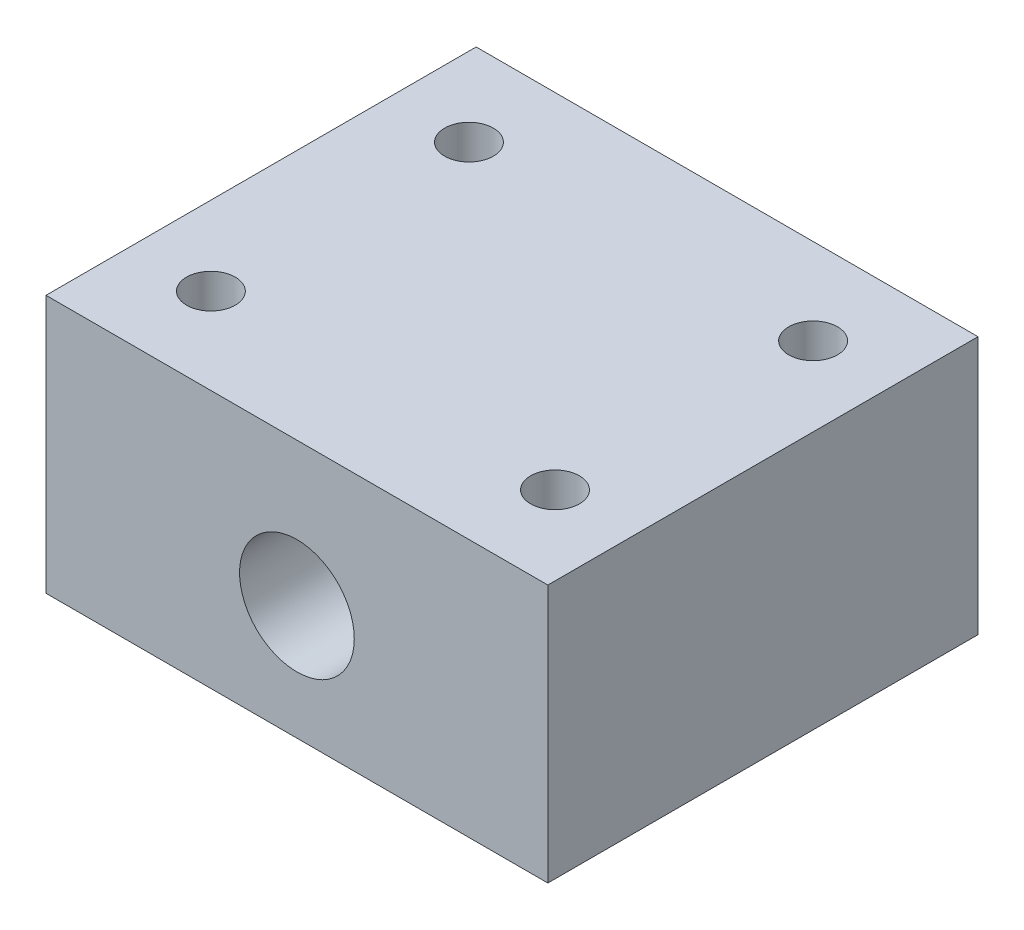
SolidWorks part; units mm, degrees
ref_plane "Front Plane" through (0, 0, 0) normal (0, 0, 1) x (1, 0, 0)
ref_plane "Top Plane" through (0, 0, 0) normal (0, 1, 0) x (1, 0, 0)
ref_plane "Right Plane" through (0, 0, 0) normal (1, 0, 0) x (0, 0, -1)
sketch "Sketch2" plane through (0, 0, 0) normal (0, 1, 0) x (1, 0, 0)
  line L0 (0, 15) -> (35, 15) construction
  line L1 (0, 0) -> (35, 0)
  line L2 (0, 0) -> (0, 30)
  line L3 (0, 30) -> (35, 30)
  line L4 (35, 0) -> (35, 30)
  line L5 (17.5, 30) -> (17.5, 0) construction
  dimension "D3" = 30
  dimension "D4" = 35
extrude "Boss-Extrude1" add sketch "Sketch2" along normal blind 18
sketch "Sketch3" plane through (0, 0, 0) normal (0, -1, 0) x (1, 0, 0)
  line L0 (17.5, 0) -> (17.5, -30) construction
  line L1 (0, 0) -> (35, 0) construction
  line L2 (35, -30) -> (0, -30) construction
  line L3 (0, -15) -> (35, -15) construction
  line L4 (0, -30) -> (0, 0) construction
  line L5 (35, 0) -> (35, -30) construction
  circle A0 centre (5.5, -24) radius 1.7
  circle A1 centre (29.5, -24) radius 1.7
  circle A2 centre (29.5, -6) radius 1.7
  circle A3 centre (5.5, -6) radius 1.7
  dimension "D1" = 3.4
  dimension "D2" = 9
  dimension "D3" = 12
extrude "Cut-Extrude1" cut sketch "Sketch3" against normal through all
sketch "Sketch4" plane through (0, 0, 0) normal (0, 0, 1) x (1, 0, 0)
  line L0 (0, 0) -> (35, 0) construction
  line L1 (17.5, 18) -> (17.5, 0) construction
  line L2 (0, 18) -> (35, 18) construction
  circle A0 centre (17.5, 8) radius 4
  dimension "D2" = 8
  dimension "D1" = 8
extrude "Cut-Extrude2" cut sketch "Sketch4" against normal through all
